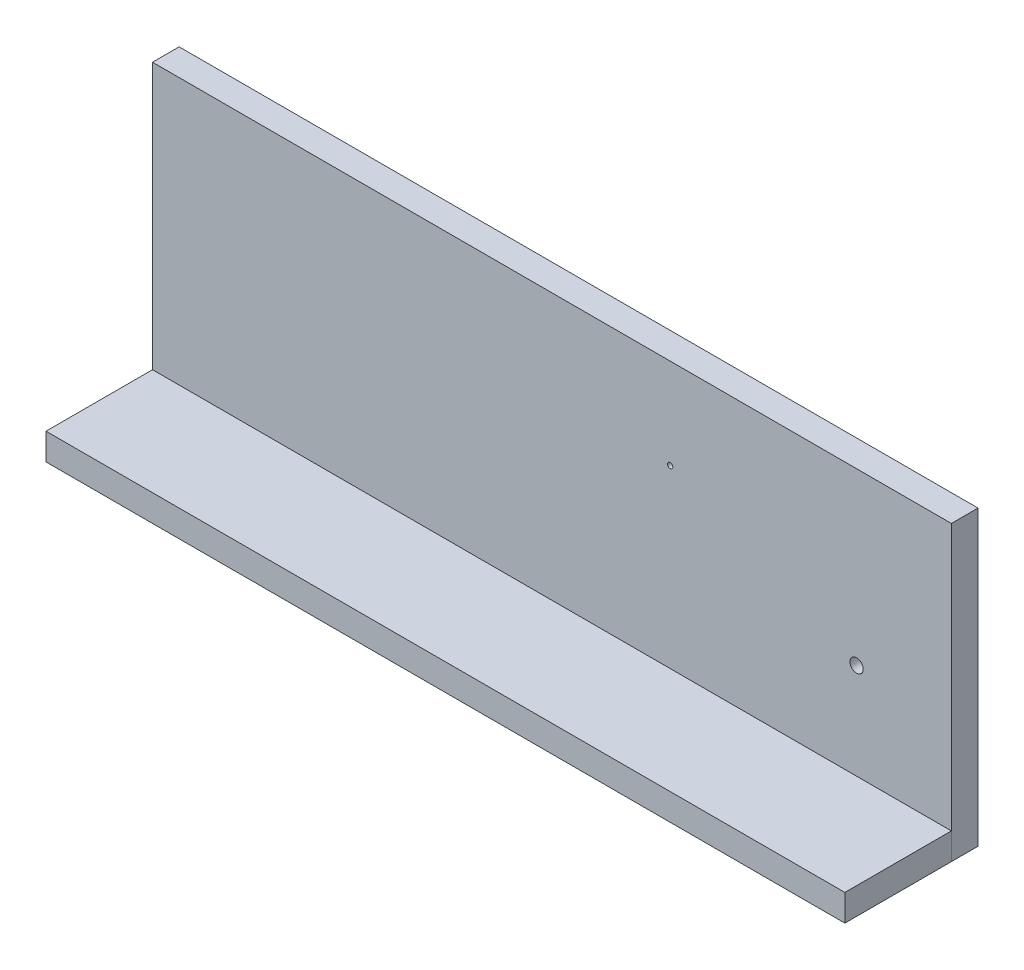
SolidWorks part; units mm, degrees
material "Gray Cast Iron"
ref_plane "Front Plane" through (0, 0, 0) normal (0, 0, 1) x (1, 0, 0)
ref_plane "Top Plane" through (0, 0, 0) normal (0, 1, 0) x (1, 0, 0)
ref_plane "Right Plane" through (0, 0, 0) normal (1, 0, 0) x (0, 0, -1)
sketch "Sketch1" plane through (0, 0, 0) normal (0, 0, 1) x (1, 0, 0)
  line L0 (0, 0) -> (0, 550)
  line L1 (0, 550) -> (1500, 550)
  line L2 (1500, 550) -> (1500, 0)
  line L3 (1500, 0) -> (0, 0)
  dimension "D1" = 550
  dimension "D2" = 1500
extrude "Boss-Extrude1" add sketch "Sketch1" against normal blind 50
sketch "Sketch2" plane through (0, 0, 0) normal (0, 0, 1) x (1, 0, 0)
  line L1 (1500, 0) -> (0, 0)
  line L2 (1500, 0) -> (1500, 50)
  line L3 (1500, 50) -> (0, 50)
  line L4 (0, 0) -> (0, 50)
  dimension "D1" = 1500
  dimension "D2" = 50
extrude "Boss-Extrude2" add sketch "Sketch2" along normal blind 200 separate body
sketch "Sketch3" plane through (0, 0, 0) normal (0, 0, 1) x (1, 0, 0)
  line L0 (1500, 230) -> (1322, 230) construction
  line L1 (1500, 50) -> (0, 50) construction
  line L2 (1500, 0) -> (1500, 550) construction
  line L3 (1500, 380) -> (972, 380) construction
  line L4 (1322, 230) -> (1322, 50) construction
  line L5 (972, 380) -> (972, 50) construction
  circle A0 centre (1322, 230) radius 12.5
  circle A1 centre (972, 380) radius 5
  dimension "D3" = 25
  dimension "D6" = 10
  dimension "D1" = 180
  dimension "D2" = 178
  dimension "D4" = 330
  dimension "D5" = 528
extrude "Cut-Extrude1" cut sketch "Sketch3" against normal through all
